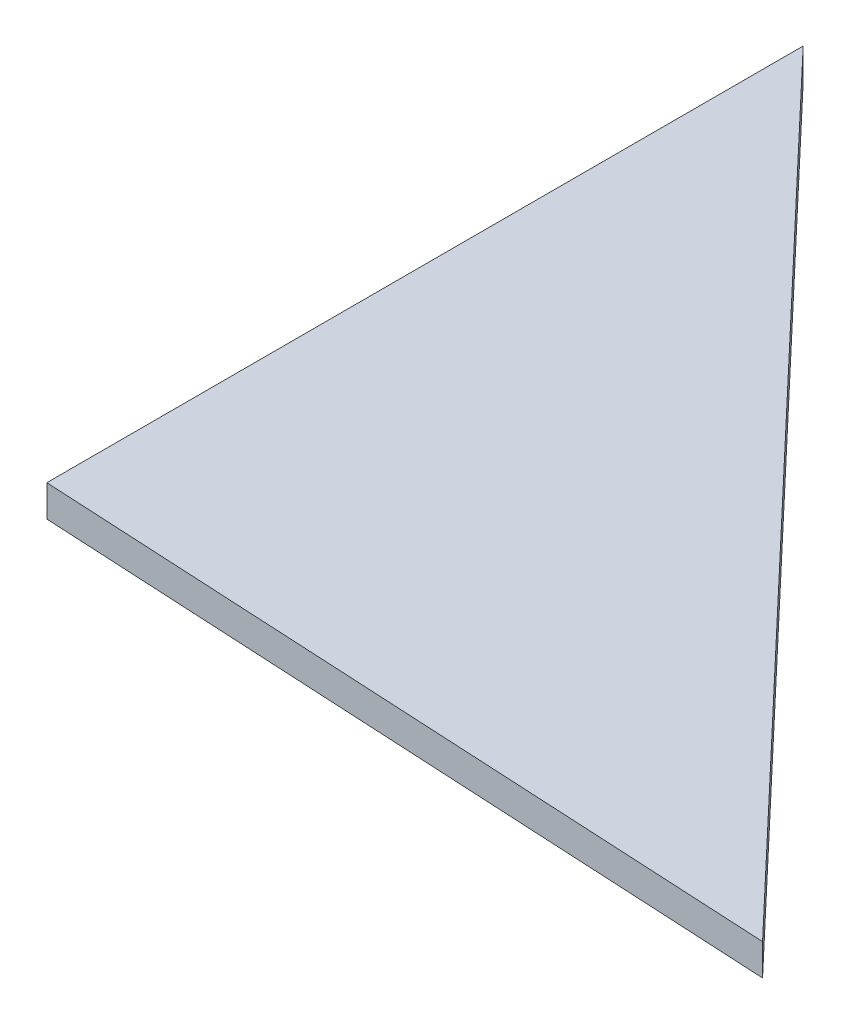
SolidWorks part; units mm, degrees
material "AISI 4130 Steel, annealed at 865C"
ref_plane "X-Y Datum" through (0, 0, 0) normal (0, 0, 1) x (1, 0, 0)
ref_plane "X-Z Datum" through (0, 0, 0) normal (0, 1, 0) x (1, 0, 0)
ref_plane "Y-Z Datum" through (0, 0, 0) normal (1, 0, 0) x (0, 0, -1)
sketch "Sketch1" plane through (0, 0, 0) normal (0, 1, 0) x (1, 0, 0)
  line L0 (-8.1065, 33.5614) -> (29.9413, -6.5326)
  line L1 (-8.1065, -4.5386) -> (29.9413, -6.5326)
  line L2 (-8.1065, -4.5386) -> (-8.1065, 33.5614)
  point P0 (34.4806, -2.3067)
  dimension "D1" = 38.1
  dimension "D2" = 93
  dimension "D3" = 38.1
extrude "Boss-Extrude1" add sketch "Sketch1" along normal blind 1.5875
